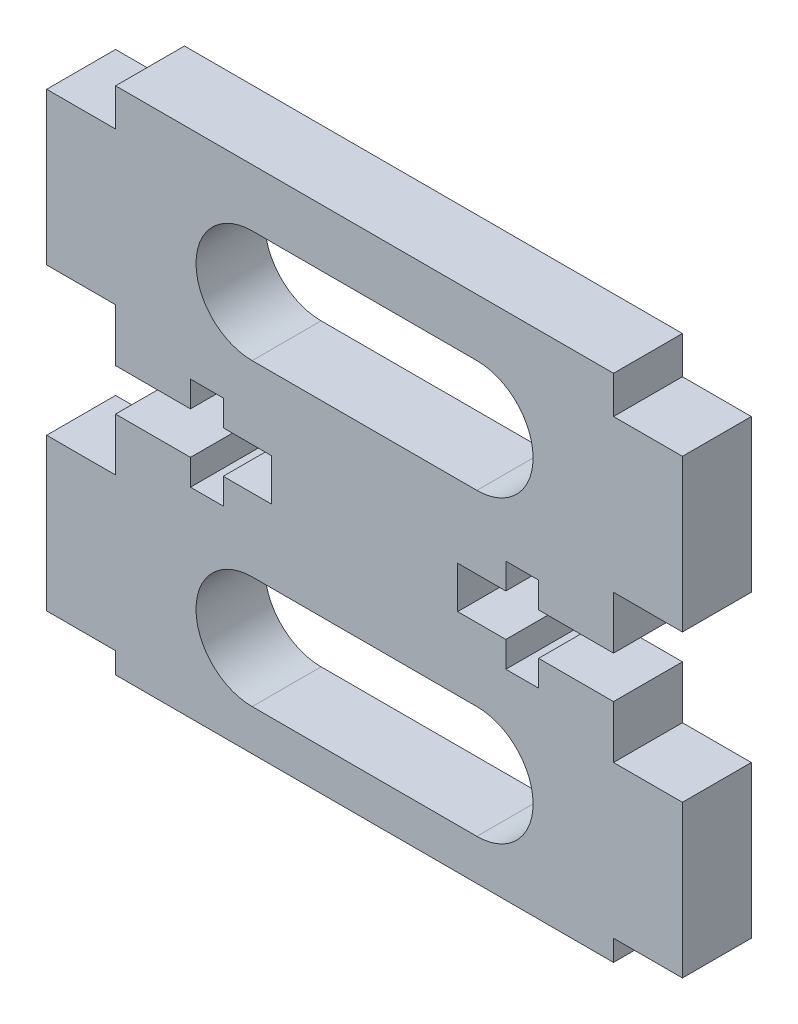
SolidWorks part; units mm, degrees
ref_plane "Front Plane" through (0, 0, 0) normal (0, 0, 1) x (1, 0, 0)
ref_plane "Top Plane" through (0, 0, 0) normal (0, 1, 0) x (1, 0, 0)
ref_plane "Right Plane" through (0, 0, 0) normal (1, 0, 0) x (0, 0, -1)
sketch "Sketch1" plane through (0, 0, 0) normal (0, 0, 1) x (1, 0, 0)
  line L0 (21.1058, 0) -> (-21.1058, 0) construction
  line L2 (21.1058, -20.928) -> (21.1058, -19.15)
  line L3 (-21.1058, -20.928) -> (21.1058, -20.928)
  line L4 (-21.1058, -20.928) -> (-21.1058, -19.15)
  line L5 (21.1058, -25.4) -> (-21.1058, 25.4) construction
  line L6 (21.1058, 25.4) -> (-21.1058, -25.4) construction
  line L7 (0, -25.4) -> (0, 25.4) construction
  line L8 (-26.9478, -19.15) -> (-21.1058, -6.25) construction
  line L9 (-26.9478, 6.25) -> (-21.1058, 6.25)
  line L10 (-26.9478, 6.25) -> (-26.9478, 19.15)
  line L11 (-26.9478, 19.15) -> (-21.1058, 19.15)
  line L12 (-21.1058, -6.25) -> (-21.1058, -1.778)
  line L13 (-26.9478, 6.25) -> (-21.1058, 19.15) construction
  line L14 (-26.9478, 19.15) -> (-21.1058, 6.25) construction
  line L15 (-26.9478, -6.25) -> (-21.1058, -19.15) construction
  line L16 (21.1058, -6.25) -> (21.1058, -1.778)
  line L17 (-26.9478, -19.15) -> (-21.1058, -19.15)
  line L18 (-26.9478, -6.25) -> (-26.9478, -19.15)
  line L19 (-26.9478, -6.25) -> (-21.1058, -6.25)
  line L20 (26.9478, -6.25) -> (21.1058, -19.15) construction
  line L21 (26.9478, 19.15) -> (21.1058, 6.25) construction
  line L22 (26.9478, 6.25) -> (21.1058, 19.15) construction
  line L23 (26.9478, -19.15) -> (21.1058, -6.25) construction
  line L24 (26.9478, -6.25) -> (21.1058, -6.25)
  line L25 (26.9478, -6.25) -> (26.9478, -19.15)
  line L26 (26.9478, -19.15) -> (21.1058, -19.15)
  line L27 (21.1058, 19.15) -> (21.1058, 22.325)
  line L28 (-21.1058, 1.778) -> (-21.1058, 6.25)
  line L29 (26.9478, 19.15) -> (21.1058, 19.15)
  line L30 (26.9478, 6.25) -> (26.9478, 19.15)
  line L31 (26.9478, 6.25) -> (21.1058, 6.25)
  line L32 (-21.1058, 19.15) -> (-21.1058, 22.325)
  line L33 (-14.7558, -1.778) -> (-21.1058, -1.778)
  line L34 (-14.7558, 1.778) -> (-14.7558, 3.9687)
  line L35 (-14.7558, 1.778) -> (-21.1058, 1.778)
  line L36 (-11.9777, 1.778) -> (-11.9777, 3.9687)
  line L37 (-14.7558, -1.778) -> (-21.1058, 1.778) construction
  line L38 (-14.7558, 1.778) -> (-21.1058, -1.778) construction
  line L39 (-11.9777, -3.9688) -> (-14.7558, -3.9688)
  line L40 (-11.9777, -3.9688) -> (-11.9777, -1.778)
  line L41 (-11.9777, 3.9687) -> (-14.7558, 3.9687)
  line L42 (-14.7558, -3.9688) -> (-14.7558, -1.778)
  line L43 (-11.9777, -3.9688) -> (-14.7558, 3.9687) construction
  line L44 (-11.9777, 3.9687) -> (-14.7558, -3.9688) construction
  line L45 (-7.8978, -1.778) -> (-11.9777, -1.778)
  line L46 (-7.8978, -1.778) -> (-7.8978, 1.778)
  line L47 (-7.8978, 1.778) -> (-11.9777, 1.778)
  line L48 (7.8978, 1.778) -> (11.9777, -1.778) construction
  line L49 (-7.8978, -1.778) -> (-11.9777, 1.778) construction
  line L50 (-7.8978, 1.778) -> (-11.9777, -1.778) construction
  line L51 (7.8978, -1.778) -> (11.9777, 1.778) construction
  line L52 (11.9777, 3.9687) -> (14.7558, -3.9688) construction
  line L53 (11.9777, -3.9688) -> (14.7558, 3.9687) construction
  line L54 (14.7558, 1.778) -> (21.1058, -1.778) construction
  line L55 (14.7558, -1.778) -> (21.1058, 1.778) construction
  line L56 (7.8978, 1.778) -> (11.9777, 1.778)
  line L57 (7.8978, -1.778) -> (7.8978, 1.778)
  line L58 (7.8978, -1.778) -> (11.9777, -1.778)
  line L59 (14.7558, -3.9688) -> (14.7558, -1.778)
  line L60 (11.9777, 3.9687) -> (14.7558, 3.9687)
  line L61 (11.9777, -3.9688) -> (11.9777, -1.778)
  line L62 (11.9777, -3.9688) -> (14.7558, -3.9688)
  line L63 (11.9777, 1.778) -> (11.9777, 3.9687)
  line L64 (14.7558, 1.778) -> (21.1058, 1.778)
  line L65 (14.7558, 1.778) -> (14.7558, 3.9687)
  line L66 (14.7558, -1.778) -> (21.1058, -1.778)
  line L67 (21.1058, 1.778) -> (21.1058, 6.25)
  line L68 (-21.1058, 22.325) -> (21.1058, 22.325)
  point P0 (0, 0)
  point P10 (-24.0268, 12.7)
  point P19 (-24.0268, -12.7)
  point P28 (24.0268, -12.7)
  point P29 (24.0268, 12.7)
  point P30 (-17.9308, 0)
  point P35 (-13.3667, 0)
  point P40 (-9.9377, 0)
  point P57 (9.9377, 0)
  point P58 (13.3667, 0)
  point P59 (17.9308, 0)
  dimension "D1" = 42.2116
  dimension "D2" = 50.8
  dimension "D3" = 5.842
  dimension "D4" = 12.9
  dimension "D5" = 12.7
  dimension "D6" = 3.556
  dimension "D7" = 7.9375
  dimension "D8" = 6.35
  dimension "D9" = 2.7781
  dimension "D10" = 3.556
  dimension "D11" = 4.0799
  dimension "D12" = 3.175
  dimension "D13" = 1.778
extrude "Boss-Extrude1" add sketch "Sketch1" along normal blind 5.842
sketch "Sketch2" plane through (0, 0, 5.842) normal (0, 0, 1) x (1, 0, 0)
  line L0 (0, 22.325) -> (0, -20.928) construction
  line L1 (21.1058, 22.325) -> (-21.1058, 22.325) construction
  line L2 (-21.1058, -20.928) -> (21.1058, -20.928) construction
  line L3 (-26.9478, 12.7) -> (26.9478, 12.7) construction
  line L4 (-26.9478, 19.15) -> (-26.9478, 6.25) construction
  line L5 (26.9478, 6.25) -> (26.9478, 19.15) construction
  line L6 (7.8978, 0) -> (-7.8978, 0) construction
  line L7 (7.8978, -1.778) -> (7.8978, 1.778) construction
  line L8 (-7.8978, 1.778) -> (-7.8978, -1.778) construction
  line L9 (-9.525, 12.7) -> (9.525, 12.7) construction
  line L10 (-9.525, 17.4625) -> (9.525, 17.4625)
  line L11 (-9.525, 7.9375) -> (9.525, 7.9375)
  line L12 (-9.525, -12.7) -> (9.525, -12.7) construction
  line L13 (-9.525, -17.4625) -> (9.525, -17.4625)
  line L14 (-9.525, -7.9375) -> (9.525, -7.9375)
  arc A0 (-9.525, 17.4625) -> (-9.525, 7.9375) centre (-9.525, 12.7) ccw
  arc A1 (9.525, 7.9375) -> (9.525, 17.4625) centre (9.525, 12.7) ccw
  arc A2 (-9.525, -17.4625) -> (-9.525, -7.9375) centre (-9.525, -12.7) cw
  arc A3 (9.525, -7.9375) -> (9.525, -17.4625) centre (9.525, -12.7) cw
  point P20 (0, 12.7)
  point P27 (0, -12.7)
  dimension "D2" = 4.7625
  dimension "D1" = 19.05
extrude "Cut-Extrude1" cut sketch "Sketch2" against normal through all
